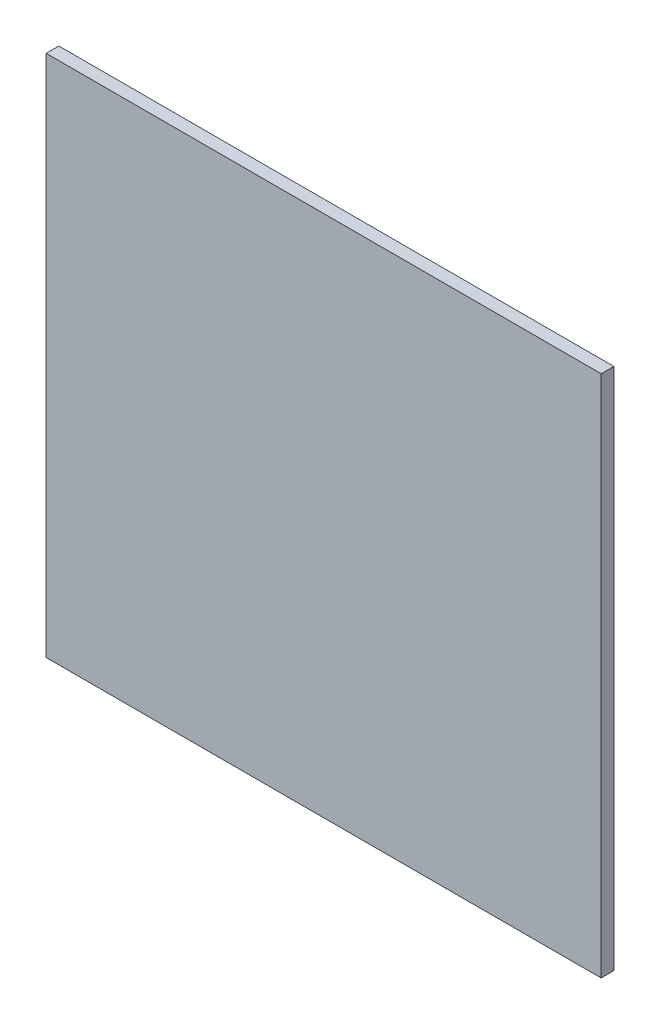
SolidWorks part; units mm, degrees
ref_plane "Front Plane" through (0, 0, 0) normal (0, 0, 1) x (1, 0, 0)
ref_plane "Top Plane" through (0, 0, 0) normal (0, 1, 0) x (1, 0, 0)
ref_plane "Right Plane" through (0, 0, 0) normal (1, 0, 0) x (0, 0, -1)
sketch "Sketch1" plane through (0, 0, 0) normal (0, 0, 1) x (1, 0, 0)
  line L1 (-34.0677, 62.1316) -> (35.9323, 62.1316)
  line L2 (-34.0677, 62.1316) -> (-34.0677, -3.8684)
  line L3 (-34.0677, -3.8684) -> (35.9323, -3.8684)
  line L4 (35.9323, 62.1316) -> (35.9323, -3.8684)
  dimension "D1" = 70
  dimension "D2" = 66
extrude "Boss-Extrude1" add sketch "Sketch1" along normal blind 1.6
